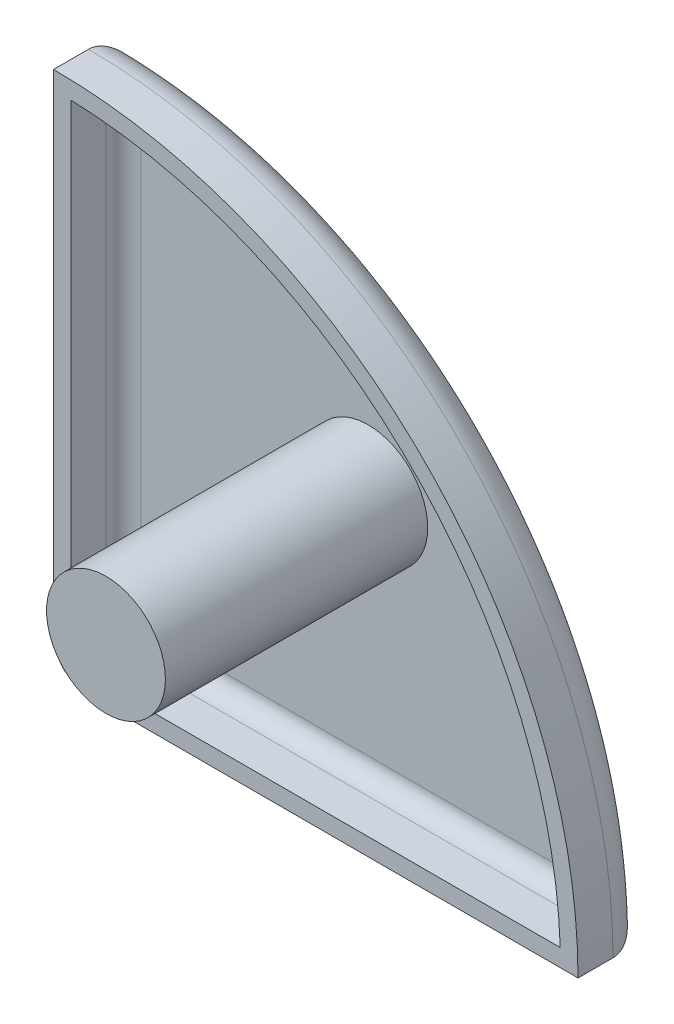
SolidWorks part; units mm, degrees
ref_plane "前视基准面" through (0, 0, 0) normal (0, 0, 1) x (1, 0, 0)
ref_plane "上视基准面" through (0, 0, 0) normal (0, 1, 0) x (1, 0, 0)
ref_plane "右视基准面" through (0, 0, 0) normal (1, 0, 0) x (0, 0, -1)
sketch "草图1" plane through (0, 0, 0) normal (0, 0, 1) x (1, 0, 0)
  line L1 (-15, 15) -> (15, 15)
  line L2 (-15, 15) -> (-15, -15)
  line L3 (-15, -15) -> (15, -15)
  line L4 (15, 15) -> (15, -15)
  line L5 (-15, 15) -> (15, -15) construction
  line L6 (-15, -15) -> (15, 15) construction
  point P0 (0, 0)
  dimension "D1" = 30
  dimension "D2" = 30
extrude "凸台-拉伸1" add sketch "草图1" along normal blind 4
sketch "草图4" plane through (0, 0, 4) normal (0, 0, 1) x (1, 0, 0)
  line L0 (15, -15) -> (15, 15) construction
  line L1 (-15, 15) -> (15, 15)
  line L2 (15, 15) -> (15, -15)
  arc A0 (-15, 15) -> (15, -15) centre (-15, -15) cw
extrude "切除-拉伸1" cut sketch "草图4" against normal through all
fillet "圆角1" radius 2 4 edges at (-15, 0, 0) (0, -15, 0) (-15, -15, 2) (6.2132, 6.2132, 0)
shell "抽壳1" thickness 1
sketch "草图2" plane through (0, 0, 1) normal (0, 0, 1) x (1, 0, 0)
  circle A0 centre (0, 0) radius 3.4
  dimension "D1" = 6.8
extrude "凸台-拉伸2" add sketch "草图2" along normal blind 15
